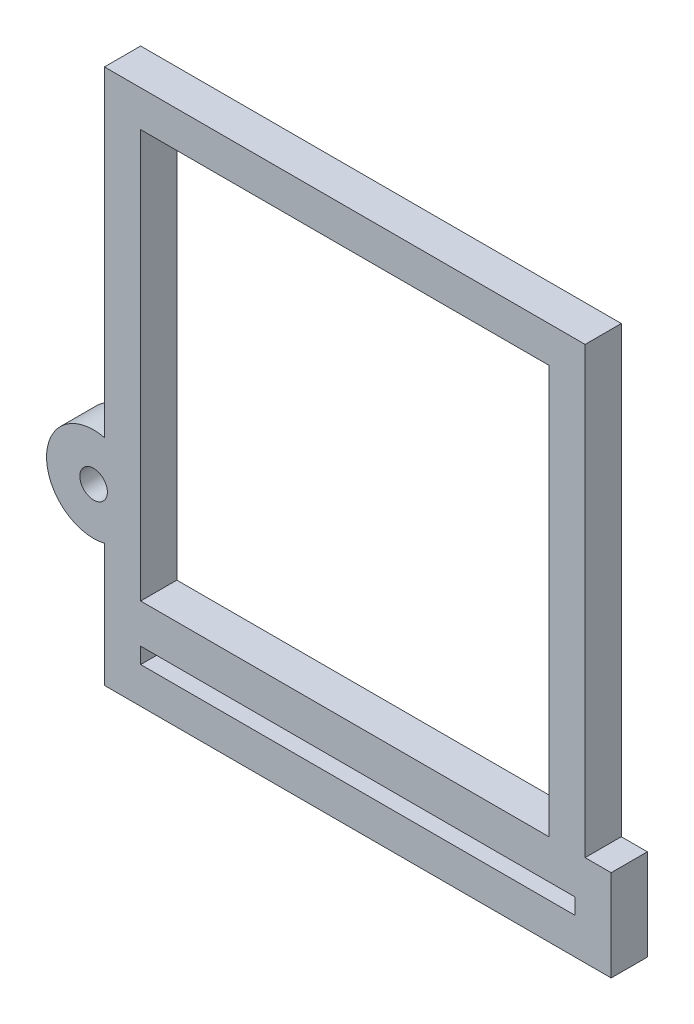
SolidWorks part; units mm, degrees
ref_plane "Спереди" through (0, 0, 0) normal (0, 0, 1) x (1, 0, 0)
ref_plane "Сверху" through (0, 0, 0) normal (0, 1, 0) x (1, 0, 0)
ref_plane "Справа" through (0, 0, 0) normal (1, 0, 0) x (0, 0, -1)
sketch "Эскиз1" plane through (0, 0, 0) normal (0, 0, 1) x (1, 0, 0)
  line L1 (0, 0) -> (70, 0)
  line L2 (0, 0) -> (0, 74)
  line L3 (0, 74) -> (70, 74)
  line L4 (70, 0) -> (70, 74)
  dimension "D1" = 74
  dimension "D2" = 70
extrude "Вытянуть1" add sketch "Эскиз1" along normal blind 5
sketch "Эскиз2" plane through (0, 0, 5) normal (0, 0, 1) x (1, 0, 0)
  line L0 (0, 0) -> (70, 0) construction
  line L1 (5, 7.2) -> (65, 7.2)
  line L2 (5, 7.2) -> (5, 5)
  line L3 (5, 5) -> (65, 5)
  line L4 (65, 7.2) -> (65, 5)
  dimension "D1" = 60
  dimension "D2" = 5
  dimension "D3" = 5
  dimension "D4" = 2.2
extrude "Вытянуть2" cut sketch "Эскиз2" against normal up to next
sketch "Эскиз3" plane through (0, 0, 5) normal (0, 0, 1) x (1, 0, 0)
  line L0 (70, 74) -> (0, 74) construction
  line L1 (5, 69) -> (61.4, 69)
  line L2 (5, 69) -> (5, 12.6)
  line L3 (5, 12.6) -> (61.4, 12.6)
  line L4 (61.4, 69) -> (61.4, 12.6)
  line L5 (0, 74) -> (0, 0) construction
  dimension "D1" = 56.4
  dimension "D2" = 5
  dimension "D3" = 5
extrude "Вытянуть3" cut sketch "Эскиз3" against normal blind 20
sketch "Эскиз4" plane through (0, 0, 0) normal (0, 0, -1) x (-1, 0, 0)
  line L0 (-61.4, 12.6) -> (-5, 12.6) construction
  line L1 (-70, 74) -> (-66.4, 74)
  line L2 (-70, 74) -> (-70, 12.6)
  line L3 (-70, 12.6) -> (-66.4, 12.6)
  line L4 (-66.4, 74) -> (-66.4, 12.6)
  line L5 (-61.4, 69) -> (-61.4, 12.6) construction
  dimension "D1" = 5
extrude "Вытянуть5" cut sketch "Эскиз4" against normal through all
sketch "Эскиз5" plane through (0, 0, 5) normal (0, 0, 1) x (1, 0, 0)
  line L0 (33.2, 12.6) -> (33.2, 69) construction
  line L1 (5, 12.6) -> (61.4, 12.6) construction
  line L2 (61.4, 69) -> (5, 69) construction
  line L3 (61.4, 40.8) -> (5, 40.8) construction
  line L4 (61.4, 12.6) -> (61.4, 69) construction
  line L5 (5, 69) -> (5, 12.6) construction
  circle A0 centre (33.2, 40.8) radius 36 construction
  circle A1 centre (33.2, 40.8) radius 31.35 construction
  circle A2 centre (33.2, 40.8) radius 32.35 construction
  circle A3 centre (-1.5, 23.3291) radius 6.5
  circle A4 centre (-1.5, 23.3291) radius 1.9 construction
  point P12 (33.2, 40.8)
  dimension "D1" = 72
  dimension "D2" = 62.7
  dimension "D3" = 64.7
  dimension "D4" = 3.8
  dimension "D5" = 13
extrude "Вытянуть6" add sketch "Эскиз5" against normal up to surface (5 mm away) up to face at (45.4667, 28.8667, 0)
sketch "Эскиз6" plane through (0, 0, 5) normal (0, 0, 1) x (1, 0, 0)
  circle A0 centre (-1.5, 23.3291) radius 1.9
  arc A1 (0, 29.6537) -> (0, 17.0045) centre (-1.5, 23.3291) ccw construction
  dimension "D1" = 3.8
extrude "Вытянуть7" cut sketch "Эскиз6" against normal up to next
